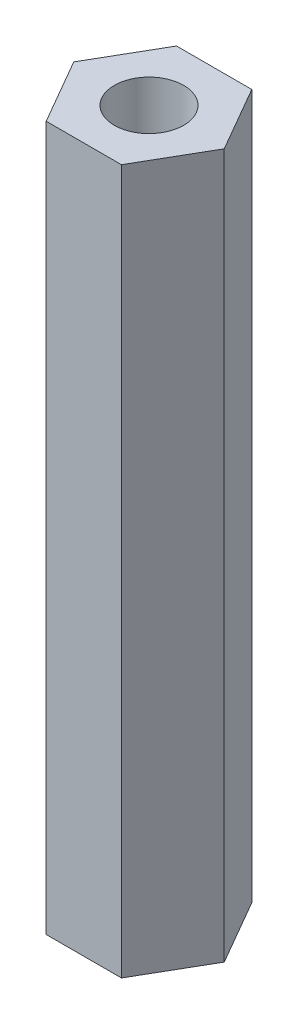
SolidWorks part; units mm, degrees
ref_plane "Front Plane" through (0, 0, 0) normal (0, 0, 1) x (1, 0, 0)
ref_plane "Top Plane" through (0, 0, 0) normal (0, 1, 0) x (1, 0, 0)
ref_plane "Right Plane" through (0, 0, 0) normal (1, 0, 0) x (0, 0, -1)
sketch "Sketch1" plane through (0, 0, 0) normal (0, 1, 0) x (1, 0, 0)
  line L1 (1.3568, 2.35) -> (-1.3568, 2.35)
  line L2 (-1.3568, 2.35) -> (-2.7135, 0)
  line L3 (-2.7135, 0) -> (-1.3568, -2.35)
  line L4 (-1.3568, -2.35) -> (1.3568, -2.35)
  line L5 (1.3568, -2.35) -> (2.7135, 0)
  line L6 (2.7135, 0) -> (1.3568, 2.35)
  circle A0 centre (0, 0) radius 2.35 construction
  circle A1 centre (0, 0) radius 1.25
  point P12 (0, 2.35)
  dimension "D2" = 2.5
  dimension "D1" = 4.7
extrude "Boss-Extrude1" add sketch "Sketch1" along normal blind 25.4
